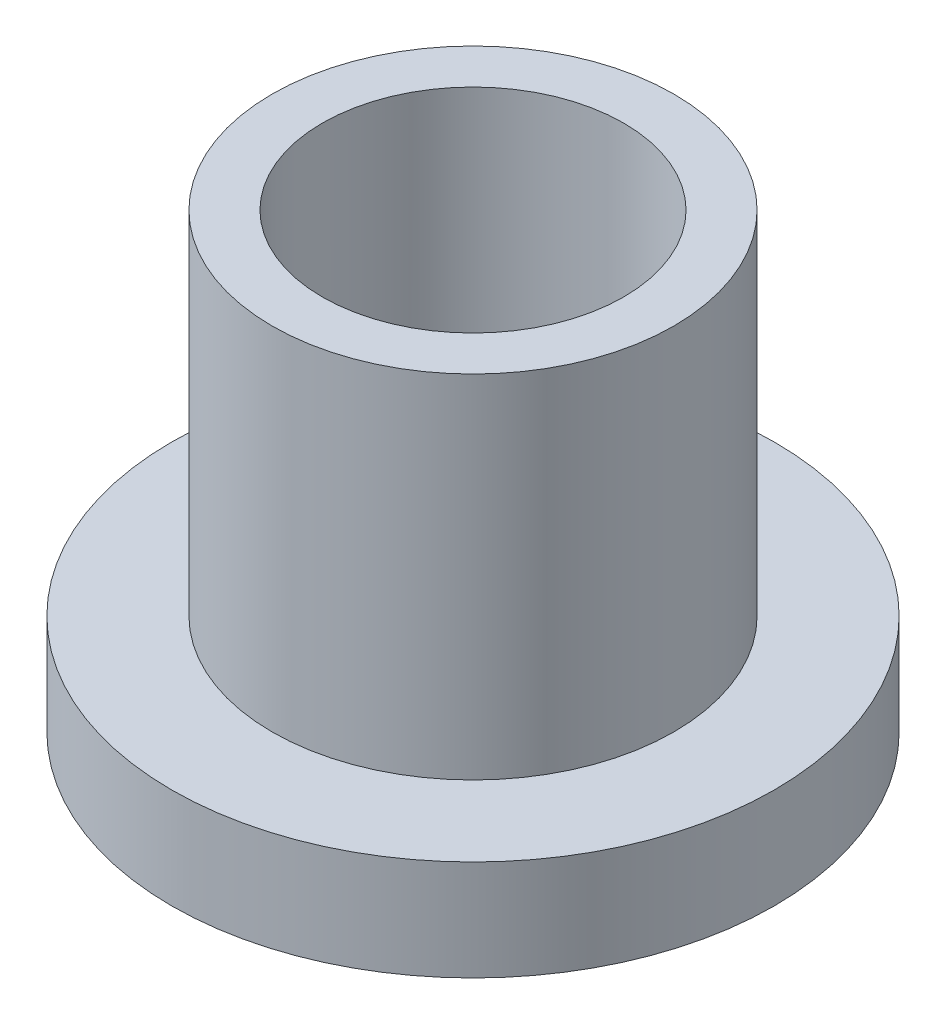
SolidWorks part; units mm, degrees
ref_plane "Alzado" through (0, 0, 0) normal (0, 0, 1) x (1, 0, 0)
ref_plane "Planta" through (0, 0, 0) normal (0, 1, 0) x (1, 0, 0)
ref_plane "Vista lateral" through (0, 0, 0) normal (1, 0, 0) x (0, 0, -1)
sketch "Croquis1" plane through (0, 0, 0) normal (0, 1, 0) x (1, 0, 0)
  circle A0 centre (0, 0) radius 4
  circle A1 centre (0, 0) radius 3
  dimension "D1" = 8
  dimension "D2" = 6
extrude "Saliente-Extruir1" add sketch "Croquis1" along normal blind 7
sketch "Croquis2" plane through (0, 0, 0) normal (0, -1, 0) x (1, 0, 0)
  circle A0 centre (0, 0) radius 3 construction
  circle A1 centre (0, 0) radius 3
  circle A2 centre (0, 0) radius 6
  dimension "D1" = 12
extrude "Saliente-Extruir2" add sketch "Croquis2" along normal blind 2
